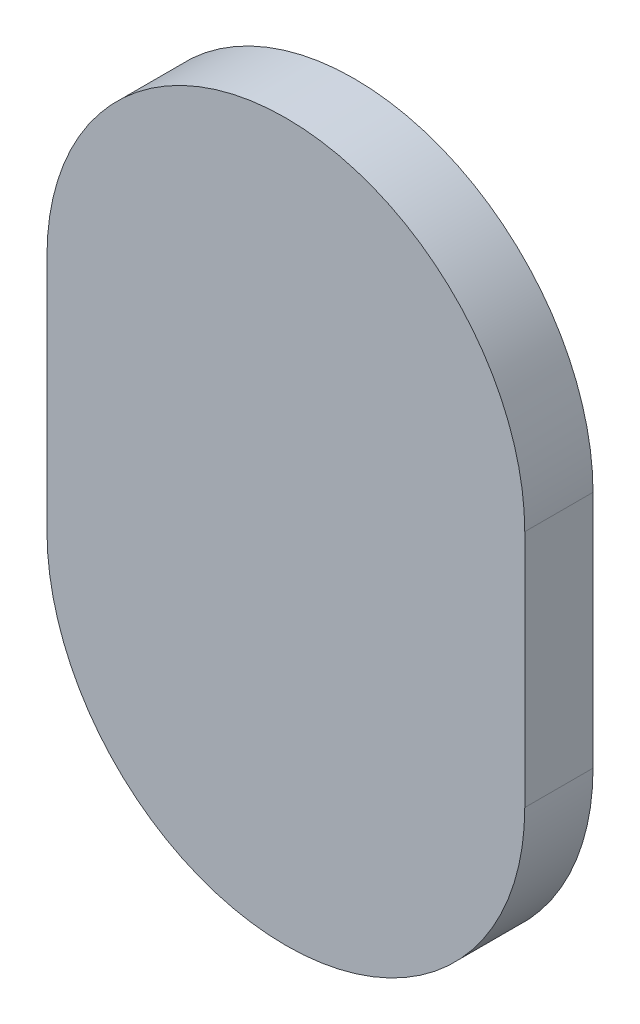
SolidWorks part; units mm, degrees
ref_plane "Спереди" through (0, 0, 0) normal (0, 0, 1) x (1, 0, 0)
ref_plane "Сверху" through (0, 0, 0) normal (0, 1, 0) x (1, 0, 0)
ref_plane "Справа" through (0, 0, 0) normal (1, 0, 0) x (0, 0, -1)
other "Configuration Table"
sketch "Эскиз1" plane through (0, 0, 0) normal (0, 0, 1) x (1, 0, 0)
  line L0 (-35, 35) -> (-35, 0)
  line L1 (35, 35) -> (35, 0)
  circle A0 centre (0, 0) radius 35
  circle A1 centre (0, 35) radius 35
  dimension "D1" = 70
  dimension "D2" = 70
  dimension "D3" = 35
extrude "Бобышка-Вытянуть1" add sketch "Эскиз1" along normal blind 10 contours A1 L0 A0 | A1 A0 | A1 A0 L1 | A0 A1 | A1 A0
equation "\"len_axes\"=30"
